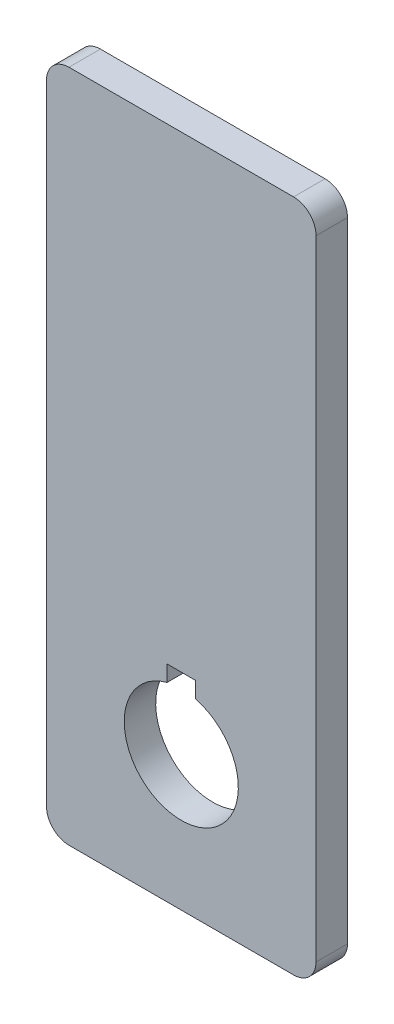
SolidWorks part; units mm, degrees
ref_plane "Alzado" through (0, 0, 0) normal (0, 0, 1) x (1, 0, 0)
ref_plane "Planta" through (0, 0, 0) normal (0, 1, 0) x (1, 0, 0)
ref_plane "Vista lateral" through (0, 0, 0) normal (1, 0, 0) x (0, 0, -1)
sketch "Croquis1" plane through (0, 0, 0) normal (0, 0, 1) x (1, 0, 0)
  line L1 (-25, -30) -> (25, -30)
  line L2 (-30, -25) -> (-30, 115)
  line L3 (-25, 120) -> (25, 120)
  line L4 (30, -25) -> (30, 115)
  circle A0 centre (0, 0) radius 12.7
  arc A1 (25, -30) -> (30, -25) centre (25, -25) ccw
  arc A2 (-25, -30) -> (-30, -25) centre (-25, -25) cw
  arc A3 (25, 120) -> (30, 115) centre (25, 115) cw
  arc A4 (-30, 115) -> (-25, 120) centre (-25, 115) cw
  point P9 (30, -30)
  point P14 (30, 120)
  dimension "D1" = 25.4
  dimension "D2" = 30
  dimension "D3" = 30
  dimension "D4" = 30
  dimension "D6" = 5
  dimension "D5" = 150
extrude "Saliente-Extruir1" add sketch "Croquis1" along normal blind 7
sketch "Croquis2" plane through (0, 0, 7) normal (0, 0, 1) x (1, 0, 0)
  line L1 (3.175, 15.875) -> (-3.175, 15.875)
  line L2 (3.175, 15.875) -> (3.175, 9.525)
  line L3 (3.175, 9.525) -> (-3.175, 9.525)
  line L4 (-3.175, 15.875) -> (-3.175, 9.525)
  line L5 (3.175, 15.875) -> (-3.175, 9.525) construction
  line L6 (3.175, 9.525) -> (-3.175, 15.875) construction
  circle A0 centre (0, 0) radius 12.7 construction
  point P0 (0, 12.7)
  dimension "D1" = 6.35
  dimension "D2" = 6.35
extrude "Cortar-Extruir1" cut sketch "Croquis2" against normal blind 10
